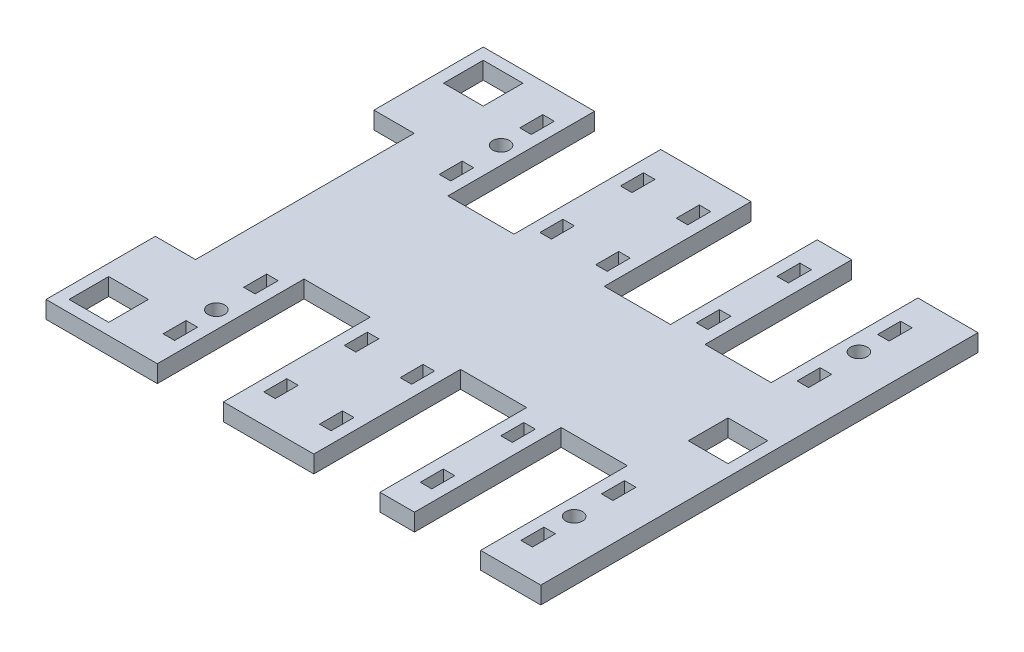
SolidWorks part; units mm, degrees
material "Chêne"
ref_plane "Plan de face" through (0, 0, 0) normal (0, 0, 1) x (1, 0, 0)
ref_plane "Plan de dessus" through (0, 0, 0) normal (0, 1, 0) x (1, 0, 0)
ref_plane "Plan de droite" through (0, 0, 0) normal (1, 0, 0) x (0, 0, -1)
sketch "Esquisse1" plane through (0, 0, 0) normal (0, 1, 0) x (1, 0, 0)
  line L0 (30.85, 0) -> (46.55, 0)
  line L1 (0, 0) -> (19.35, 0)
  line L2 (0, 0) -> (0, 19)
  line L3 (75.55, 0) -> (86, 0)
  line L4 (86, 0) -> (86, 76)
  line L5 (-1003.8634, 38) -> (7, 38) construction
  line L6 (60.05, 9) -> (62.05, 9)
  line L7 (15.35, 9) -> (17.35, 9)
  line L8 (15.35, 9) -> (15.35, 5)
  line L9 (15.35, 5) -> (17.35, 5)
  line L10 (17.35, 9) -> (17.35, 5)
  line L11 (77.1, 41.45) -> (77.1, 34.55)
  line L12 (77.1, 34.55) -> (84, 34.55)
  line L13 (84, 41.45) -> (84, 34.55)
  line L14 (32.85, 9) -> (34.85, 9)
  line L15 (60.05, 9) -> (60.05, 5)
  line L16 (60.05, 5) -> (62.05, 5)
  line L17 (62.05, 9) -> (62.05, 5)
  line L18 (2, 2) -> (8.9, 2)
  line L19 (2, 2) -> (2, 8.9)
  line L20 (2, 8.9) -> (8.9, 8.9)
  line L21 (8.9, 2) -> (8.9, 8.9)
  line L22 (32.85, 9) -> (32.85, 5)
  line L23 (32.85, 5) -> (34.85, 5)
  line L24 (34.85, 9) -> (34.85, 5)
  line L25 (32.85, 23) -> (34.85, 23)
  line L26 (32.85, 23) -> (32.85, 19)
  line L27 (30.85, 0) -> (30.85, 25.5)
  line L28 (30.85, 25.5) -> (19.35, 25.5)
  line L29 (19.35, 0) -> (19.35, 25.5)
  line L30 (32.85, 19) -> (34.85, 19)
  line L31 (34.85, 23) -> (34.85, 19)
  line L32 (15.35, 23) -> (17.35, 23)
  line L33 (15.35, 23) -> (15.35, 19)
  line L34 (15.35, 19) -> (17.35, 19)
  line L35 (17.35, 23) -> (17.35, 19)
  line L36 (77.55, 9) -> (79.55, 9)
  line L37 (77.55, 9) -> (77.55, 5)
  line L38 (77.55, 5) -> (79.55, 5)
  line L39 (79.55, 9) -> (79.55, 5)
  line L40 (77.55, 23) -> (79.55, 23)
  line L41 (77.55, 23) -> (77.55, 19)
  line L42 (75.55, 0) -> (75.55, 25.5)
  line L43 (75.55, 25.5) -> (64.05, 25.5)
  line L44 (64.05, 0) -> (64.05, 25.5)
  line L45 (77.55, 19) -> (79.55, 19)
  line L46 (79.55, 23) -> (79.55, 19)
  line L47 (60.05, 23) -> (62.05, 23)
  line L48 (60.05, 23) -> (60.05, 19)
  line L49 (60.05, 19) -> (62.05, 19)
  line L50 (62.05, 23) -> (62.05, 19)
  line L51 (7, 38) -> (50004.5782, 38) construction
  line L52 (0, 19) -> (7, 19)
  line L53 (0, 57) -> (7, 57)
  line L54 (62.05, 53) -> (62.05, 57)
  line L55 (7, 19) -> (7, 57)
  line L56 (60.05, 57) -> (62.05, 57)
  line L57 (60.05, 53) -> (60.05, 57)
  line L58 (60.05, 53) -> (62.05, 53)
  line L59 (79.55, 53) -> (79.55, 57)
  line L60 (77.55, 57) -> (79.55, 57)
  line L61 (64.05, 76) -> (64.05, 50.5)
  line L62 (75.55, 50.5) -> (64.05, 50.5)
  line L63 (75.55, 76) -> (75.55, 50.5)
  line L64 (77.55, 53) -> (77.55, 57)
  line L65 (77.55, 53) -> (79.55, 53)
  line L66 (79.55, 67) -> (79.55, 71)
  line L67 (77.55, 71) -> (79.55, 71)
  line L68 (77.55, 67) -> (77.55, 71)
  line L69 (77.55, 67) -> (79.55, 67)
  line L70 (17.35, 53) -> (17.35, 57)
  line L71 (15.35, 57) -> (17.35, 57)
  line L72 (15.35, 53) -> (15.35, 57)
  line L73 (15.35, 53) -> (17.35, 53)
  line L74 (34.85, 53) -> (34.85, 57)
  line L75 (32.85, 57) -> (34.85, 57)
  line L76 (19.35, 76) -> (19.35, 50.5)
  line L77 (30.85, 50.5) -> (19.35, 50.5)
  line L78 (30.85, 76) -> (30.85, 50.5)
  line L79 (32.85, 53) -> (32.85, 57)
  line L80 (32.85, 53) -> (34.85, 53)
  line L81 (34.85, 67) -> (34.85, 71)
  line L82 (32.85, 71) -> (34.85, 71)
  line L83 (32.85, 67) -> (32.85, 71)
  line L84 (8.9, 74) -> (8.9, 67.1)
  line L85 (2, 67.1) -> (8.9, 67.1)
  line L86 (2, 74) -> (2, 67.1)
  line L87 (2, 74) -> (8.9, 74)
  line L88 (62.05, 67) -> (62.05, 71)
  line L89 (60.05, 71) -> (62.05, 71)
  line L90 (60.05, 67) -> (60.05, 71)
  line L91 (32.85, 67) -> (34.85, 67)
  line L92 (77.1, 41.45) -> (84, 41.45)
  line L93 (17.35, 67) -> (17.35, 71)
  line L94 (15.35, 71) -> (17.35, 71)
  line L95 (15.35, 67) -> (15.35, 71)
  line L96 (15.35, 67) -> (17.35, 67)
  line L97 (60.05, 67) -> (62.05, 67)
  line L98 (75.55, 76) -> (86, 76)
  line L99 (0, 76) -> (0, 57)
  line L100 (0, 76) -> (19.35, 76)
  line L101 (30.85, 76) -> (46.55, 76)
  line L102 (58.05, 0) -> (64.05, 0)
  line L103 (58.05, 76) -> (58.05, 50.5)
  line L104 (46.55, 0) -> (46.55, 25.5)
  line L105 (46.55, 25.5) -> (58.05, 25.5)
  line L106 (58.05, 0) -> (58.05, 25.5)
  line L107 (46.55, 50.5) -> (58.05, 50.5)
  line L108 (46.55, 76) -> (46.55, 50.5)
  line L109 (58.05, 76) -> (64.05, 76)
  line L110 (44.55, 53) -> (44.55, 57)
  line L111 (42.55, 9) -> (44.55, 9)
  line L112 (42.55, 9) -> (42.55, 5)
  line L113 (42.55, 5) -> (44.55, 5)
  line L114 (44.55, 9) -> (44.55, 5)
  line L115 (42.55, 23) -> (44.55, 23)
  line L116 (42.55, 23) -> (42.55, 19)
  line L117 (42.55, 19) -> (44.55, 19)
  line L118 (44.55, 23) -> (44.55, 19)
  line L119 (42.55, 57) -> (44.55, 57)
  line L120 (42.55, 53) -> (42.55, 57)
  line L121 (42.55, 53) -> (44.55, 53)
  line L122 (44.55, 67) -> (44.55, 71)
  line L123 (42.55, 71) -> (44.55, 71)
  line L124 (42.55, 67) -> (42.55, 71)
  line L125 (42.55, 67) -> (44.55, 67)
  circle A0 centre (16.35, 13.25) radius 1.45
  circle A1 centre (78.55, 13.25) radius 1.45
  circle A2 centre (78.55, 62.75) radius 1.45
  circle A3 centre (16.35, 62.75) radius 1.45
  point P110 (84, 38)
  point P111 (77.1, 38)
  point P116 (86, 38)
  point P123 (78.55, 9)
  point P124 (16.35, 9)
  dimension "D2" = 38
  dimension "D24" = 2.9
  dimension "D25" = 2.9
  dimension "D28" = 2
  dimension "D29" = 7.45
  dimension "D3" = 86
  dimension "D4" = 2
  dimension "D5" = 2
  dimension "D6" = 6.9
  dimension "D7" = 11.5
  dimension "D8" = 25.5
  dimension "D9" = 62.2
  dimension "D10" = 2
  dimension "D11" = 4
  dimension "D12" = 5
  dimension "D13" = 10
  dimension "D14" = 2
  dimension "D15" = 2
  dimension "D16" = 2
  dimension "D17" = 10
  dimension "D18" = 2
  dimension "D19" = 2
  dimension "D20" = 2
  dimension "D21" = 2
  dimension "D22" = 19
  dimension "D23" = 7
  dimension "D26" = 3.45
  dimension "D27" = 24.75
  dimension "D30" = 2
extrude "Boss.-Extru.1" add sketch "Esquisse1" along normal blind 3
